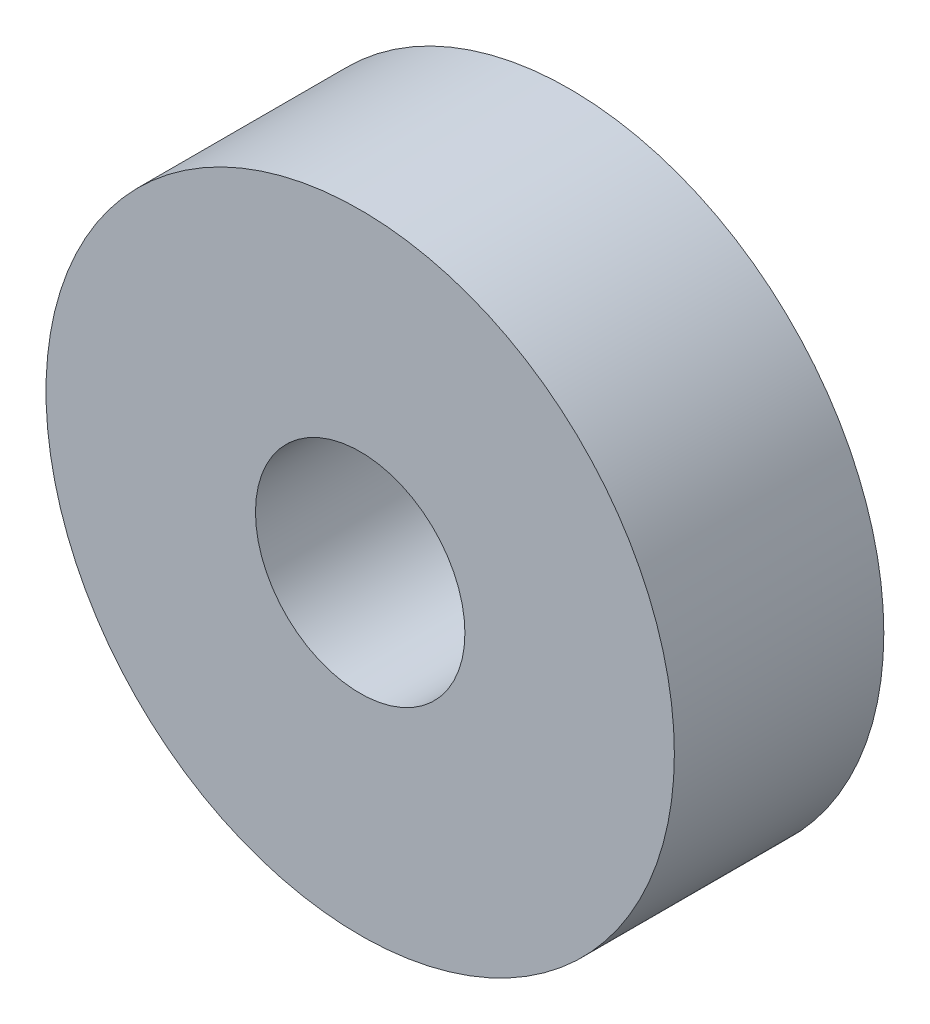
SolidWorks part; units mm, degrees
ref_plane "前视基准面" through (0, 0, 0) normal (0, 0, 1) x (1, 0, 0)
ref_plane "上视基准面" through (0, 0, 0) normal (0, 1, 0) x (1, 0, 0)
ref_plane "右视基准面" through (0, 0, 0) normal (1, 0, 0) x (0, 0, -1)
sketch "草图1" plane through (0, 0, 0) normal (0, 0, 1) x (1, 0, 0)
  circle A0 centre (0, 0) radius 12
  circle A1 centre (0, 0) radius 4
  dimension "D1" = 8
  dimension "D2" = 24
extrude "拉伸1" add sketch "草图1" along normal blind 8
